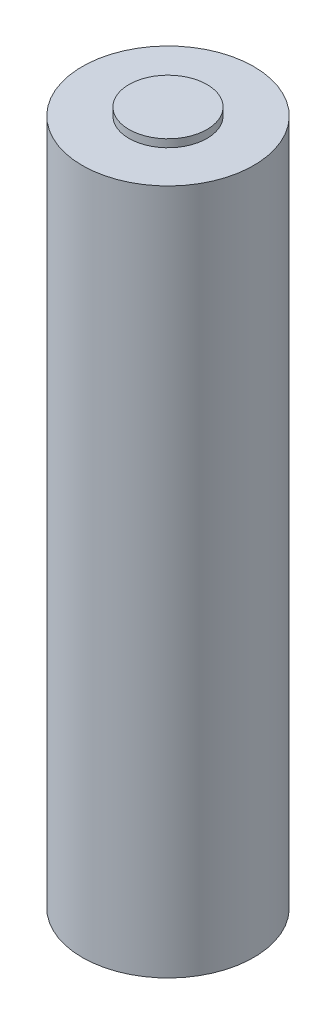
SolidWorks part; units mm, degrees
ref_plane "Front Plane" through (0, 0, 0) normal (0, 0, 1) x (1, 0, 0)
ref_plane "Top Plane" through (0, 0, 0) normal (0, 1, 0) x (1, 0, 0)
ref_plane "Right Plane" through (0, 0, 0) normal (1, 0, 0) x (0, 0, -1)
sketch "Sketch1" plane through (0, 0, 0) normal (0, 1, 0) x (1, 0, 0)
  circle A0 centre (0, 0) radius 5.5
  dimension "D1" = 11
extrude "Extrude1" add sketch "Sketch1" along normal blind 44
sketch "Sketch2" plane through (0, 44, 0) normal (0, 1, 0) x (-1, 0, 0)
  circle A0 centre (0, 0) radius 2.5
  circle A1 centre (0, 0) radius 5.5 construction
  dimension "D1" = 5
extrude "Extrude2" add sketch "Sketch2" along normal blind 0.5
